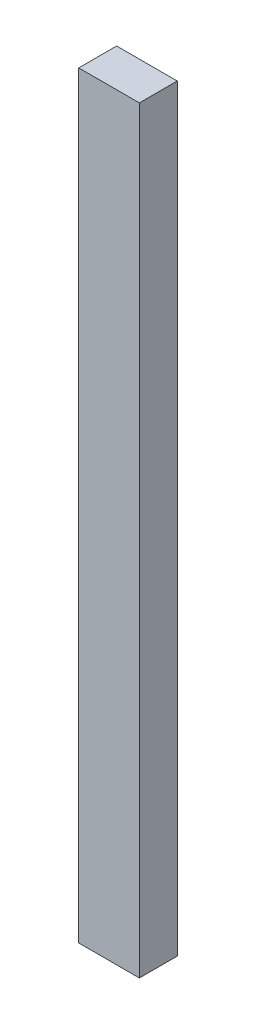
SolidWorks part; units mm, degrees
ref_plane "Plan de face" through (0, 0, 0) normal (0, 0, 1) x (1, 0, 0)
ref_plane "Plan de dessus" through (0, 0, 0) normal (0, 1, 0) x (1, 0, 0)
ref_plane "Plan de droite" through (0, 0, 0) normal (1, 0, 0) x (0, 0, -1)
sketch "Esquisse1" plane through (0, 0, 0) normal (0, 0, 1) x (1, 0, 0)
  line L1 (0, 0) -> (40, 0)
  line L2 (0, 0) -> (0, 500)
  line L3 (0, 500) -> (40, 500)
  line L4 (40, 0) -> (40, 500)
  dimension "D1" = 40
  dimension "D2" = 500
extrude "Boss.-Extru.1" add sketch "Esquisse1" along normal blind 25
